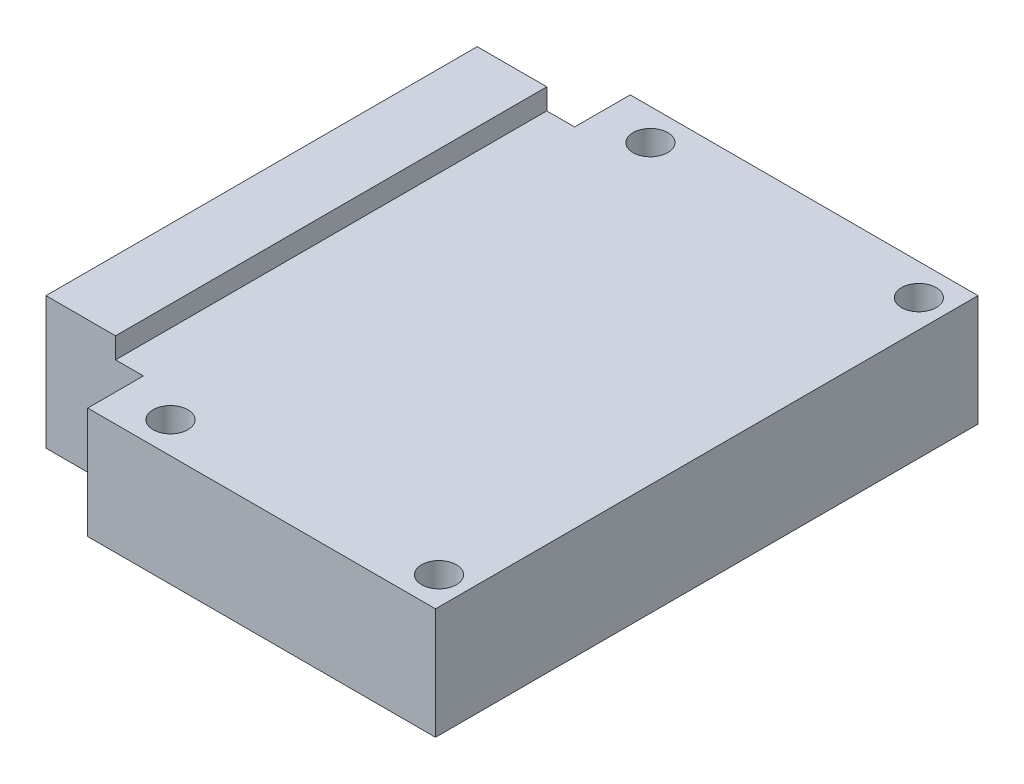
SolidWorks part; units mm, degrees
ref_plane "前视基准面" through (0, 0, 0) normal (0, 0, 1) x (1, 0, 0)
ref_plane "上视基准面" through (0, 0, 0) normal (0, 1, 0) x (1, 0, 0)
ref_plane "右视基准面" through (0, 0, 0) normal (1, 0, 0) x (0, 0, -1)
sketch "草图2" plane through (0, 0, 0) normal (0, 1, 0) x (1, 0, 0)
  line L0 (-18, 39) -> (-18, 31)
  line L1 (32, -39) -> (-18, -39)
  line L2 (32, -39) -> (32, 39)
  line L3 (32, 39) -> (-18, 39)
  line L4 (-32, -31) -> (-32, 31)
  line L5 (32, -39) -> (-32, 39) construction
  line L6 (32, 39) -> (-32, -39) construction
  line L7 (-18, 31) -> (-32, 31)
  line L8 (-32, 31) -> (-18, 31)
  line L9 (-18, -39) -> (-18, -31)
  line L10 (-18, -31) -> (-32, -31)
  circle A0 centre (28, 34.5) radius 2.5
  circle A1 centre (-10.6, 34.5) radius 2.5
  circle A2 centre (28, -34.5) radius 2.5
  circle A3 centre (-10.6, -34.5) radius 2.5
  point P0 (0, 0)
  dimension "D6" = 5
  dimension "D9" = 5
  dimension "D1" = 64
  dimension "D2" = 78
  dimension "D3" = 8
  dimension "D4" = 14
  dimension "D5" = 8
  dimension "D7" = 4
  dimension "D8" = 4.5
  dimension "D10" = 38.6
  dimension "D11" = 4.5
extrude "凸台-拉伸2" add sketch "草图2" along normal blind 16 contours L10 L9 L1 L2 L3 L0 L7 L4
sketch "草图5" plane through (0, 16, 0) normal (0, 1, 0) x (1, 0, 0)
  line L0 (-18, -31) -> (-32, -31) construction
  line L1 (-32, 31) -> (-22, 31)
  line L2 (-32, 31) -> (-32, -31)
  line L3 (-32, -31) -> (-22, -31)
  line L4 (-22, 31) -> (-22, -31)
  dimension "D1" = 10
extrude "凸台-拉伸3" add sketch "草图5" along normal blind 3
